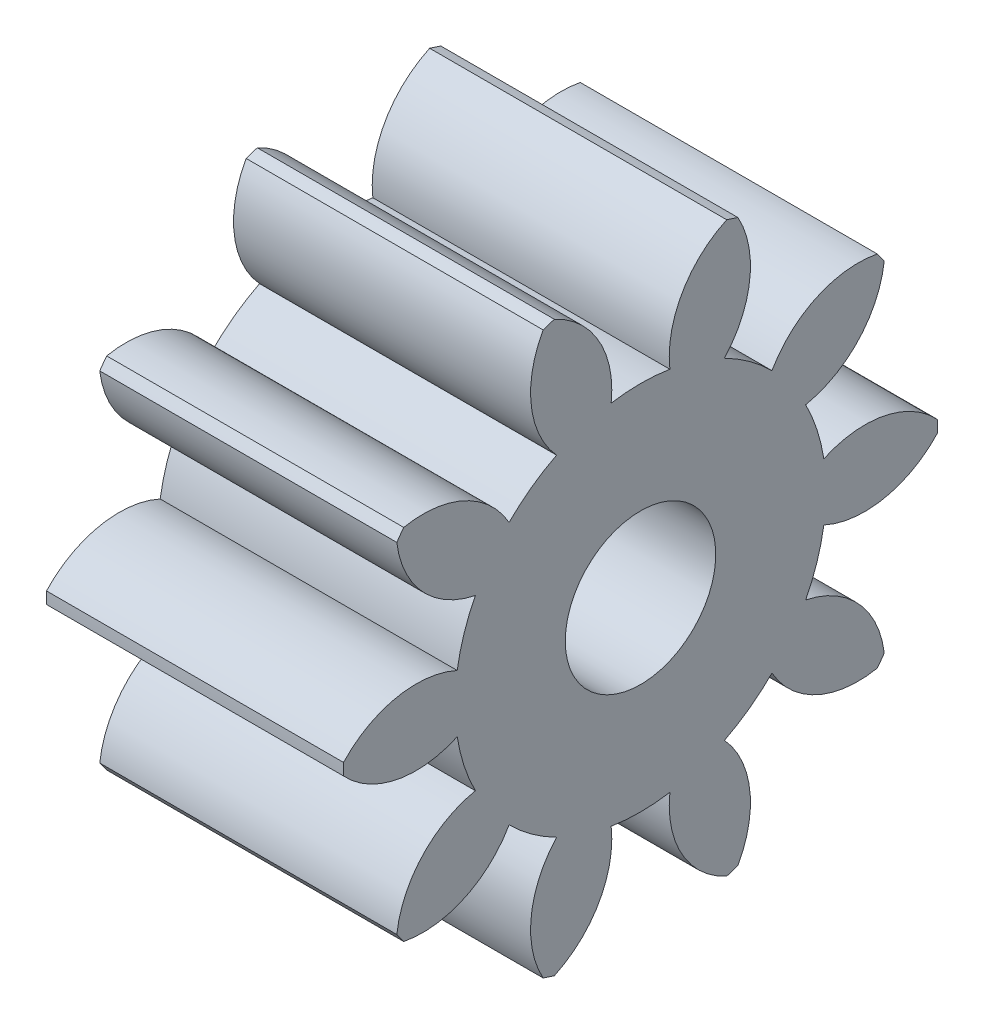
SolidWorks part; units mm, degrees
ref_plane "Plane1" through (0, 0, 0) normal (0, 0, 1) x (1, 0, 0)
ref_plane "Plane2" through (0, 0, 0) normal (0, 1, 0) x (1, 0, 0)
ref_plane "Plane3" through (0, 0, 0) normal (1, 0, 0) x (0, 0, -1)
other "Configuration Table"
sketch "HoldingSke" plane through (0, 0, 0) normal (0, 1, 0) x (1, 0, 0)
  line L0 (0, 0) -> (1.9696, -0.3473)
  line L1 (-15, 0) -> (100, 0) construction
  line L2 (0, 0) -> (-2.1039, 2.3779)
  line L3 (0, 0) -> (-11.863, 4.5341)
  line L4 (0, 0) -> (8.5048, 1.4996)
  line L5 (0, 0) -> (-46.8476, -17.4728)
  line L6 (0, 0) -> (-2.4869, -1.6779)
  line L7 (-2.1039, 2.3779) -> (8.6586, 51.2059)
  line L8 (-76.2, 54.61) -> (-76, 54.61)
  line L9 (-71.009, 38.7566) -> (-53.1078, 45.2721)
  line L10 (-76.2, 71.12) -> (104.1128, 71.12)
  line L11 (0, 0) -> (-3, 0)
  line L12 (-76.2, 101.6) -> (-76.181, 101.6)
  line L13 (24.9733, 27.94) -> (52.9518, 28.4284)
  line L14 (24.9733, 27.94) -> (24.9743, 27.94)
  line L15 (24.9733, 27.94) -> (100.4006, 29.5858)
  line L16 (-63.627, -0.5) -> (-12.827, -0.5)
  circle A0 centre (0, 0) radius 0.75
  circle A1 centre (0, 0) radius 1.874
  circle A2 centre (0, 0) radius 37.5
  circle A3 centre (0, 0) radius 0.75
  dimension "MHD" = 3.748
  dimension "Hub_dia" = 75
  dimension "Bore" = 1.5
  dimension "MBD" = 1.5
  dimension "Num_teeth" = 10
  dimension "Pitch" = 2
  dimension "Overall_len" = 50
  dimension "Show_teeth" = 10
  dimension "Thickness" = 3
  dimension "OAL" = 50.0001
  dimension "T_dim" = 0.2
  dimension "Ap" = 20
  dimension "H" = 19.05
  dimension "Pitch_radius" = 180.3128
  dimension "Width" = 3
  dimension "Backlash" = 0.019
  dimension "Addendum_fac" = 1
  dimension "Dedendum_fac" = 1.25
  dimension "Clearance_fac" = 0.25
  dimension "Dedendum_add" = 0.001
  dimension "Module" = 0.5
sketch "BasProSke" plane through (0, 0, 0) normal (0, 1, 0) x (1, 0, 0)
  line L0 (-10, 0) -> (60, 0) construction
  line L1 (0, 0) -> (0, 3)
  line L2 (0, 0) -> (3, 0)
  line L3 (3, 0) -> (3, 3)
  line L4 (3, 3) -> (0, 3)
  dimension "Thickness" = 3
  dimension "Diameter" = 6
revolve "Base-Revolve" add sketch "BasProSke" angle 360 about L0
sketch "TooCutSke" plane through (0, 0, 0) normal (1, 0, 0) x (0, 0, -1)
  line L1 (0, 0) -> (0, 107) construction
  line L2 (0, 0) -> (-0.4243, 2.4637) construction
  line L3 (0, 0) -> (-1.5292, 4.7063) construction
  line L4 (-0.4243, 2.4637) -> (-0.7646, 2.3532) construction
  arc A0 (0.2964, 1.8504) -> (-0.2964, 1.8504) centre (0, 0) ccw
  arc A1 (0.9059, 2.8866) -> (-0.9059, 2.8866) centre (0, 0) ccw
  circle A2 centre (0, 0) radius 2.5 construction
  circle A3 centre (0, 0) radius 2.3492 construction
  arc A4 (-0.2964, 1.8504) -> (-0.9059, 2.8866) centre (-1.2901, 1.9633) ccw
  arc A5 (0.9059, 2.8866) -> (0.2964, 1.8504) centre (1.2901, 1.9633) ccw
  dimension "Root_dia" = 3.748
  dimension "Overcut_dia" = 6.0508
  dimension "Pitch_dia" = 5
  dimension "Base_dia" = 4.6985
  dimension "Flank_rad" = 1
  dimension "Half_ang" = 18
  dimension "Half_CT" = 0.3578
extrude "ToothCut" cut sketch "TooCutSke" along normal through all
fillet "Breaks" [suppressed] radius 0.01
fillet "RootFillets" [suppressed] radius 0.126
pattern_circular "TeethCuts" count 10 every 36 about axis through (-10, 0, 0) along (1, 0, 0) of "ToothCut", "RootFillets", "Breaks"
sketch "HubNeaOneSke" plane through (0, 0, 0) normal (-1, 0, 0) x (0, 0, 1)
  circle A0 centre (0, 0) radius 1.874
  dimension "Diameter" = 3.748
extrude "HubNearOne" [suppressed] add sketch "HubNeaOneSke" along normal blind 47.0001
sketch "HubNeaBotSke" plane through (0, 0, 0) normal (-1, 0, 0) x (0, 0, 1)
  circle A0 centre (0, 0) radius 1.874
  dimension "Diameter" = 3.748
extrude "HubNearBoth" [suppressed] add sketch "HubNeaBotSke" along normal blind 23.5001
ref_plane "FarPln" through (3, 0, 0) normal (1, 0, 0) x (0, 0, -1)
sketch "HubFarSke" plane through (3, 0, 0) normal (1, 0, 0) x (0, 0, -1)
  circle A0 centre (0, 0) radius 1.874
  dimension "Diameter" = 3.748
extrude "HubFar" [suppressed] add sketch "HubFarSke" along normal blind 23.5001
sketch "BorSke" plane through (0, 0, 0) normal (1, 0, 0) x (0, 0, -1)
  circle A0 centre (0, 0) radius 0.76
  dimension "Diameter" = 1.52
extrude "Bore" cut sketch "BorSke" along normal mid plane 100.0002
sketch "KeySke" plane through (0, 0, 0) normal (1, 0, 0) x (0, 0, -1)
  line L0 (-0.3, 0) -> (-0.3, 0.95)
  line L1 (-0.3, 0.95) -> (0.3, 0.95)
  line L2 (0.3, 0.95) -> (0.3, 0)
  line L3 (0, 0) -> (0, 34) construction
  line L4 (-0.3, 0) -> (0.3, 0)
  dimension "Offset" = 0.95
  dimension "Width" = 0.6
extrude "Keyway" [suppressed] cut sketch "KeySke" along normal mid plane 100.0002
pattern_circular "Keyway2" [suppressed] count 2 every 90 about axis through (-10, 0, 0) along (1, 0, 0)
equation "' \"Module@HoldingSke\" = 6.35"
equation "' \"Num_teeth@HoldingSke\" = 12"
equation "' \"Ap@HoldingSke\" =  20"
equation "' \"Ap@HoldingSke\" = 20"
equation "' \"Width@HoldingSke\" = 0.5 * 25.4"
equation "' \"Hub_dia@HoldingSke\"= 1 * 25.4"
equation "' \"Hub_dia@HoldingSke\" = 1 * 25.4"
equation "' \"Overall_len@HoldingSke\" = 1.0 * 25.4"
equation "' \"Bore@HoldingSke\" = 0.75 * 25.4"
equation "' \"T_dim@HoldingSke\" = 0.1 * 25.4"
equation "' \"Width@KeySke\" = 0.25 * 25.4"
equation "' \"Show_teeth@HoldingSke\" = 13"
equation "' \"Backlash@HoldingSke\" = 0.009 * 25.4"
equation "' \"Addendum_fac@HoldingSke\" = 1.0"
equation "' \"Dedendum_fac@HoldingSke\" = 1.25"
equation "' \"Dedendum_add@HoldingSke\" = 0.00005 * 25.4"
equation "' \"Clearance_fac@HoldingSke\" = 0.25"
equation "\"Pitch@HoldingSke\" = 1 / \"Module@HoldingSke\""
equation "\"Overcut_dia@TooCutSke\" = (\"Num_teeth@HoldingSke\" + 2 * \"Addendum_fac@HoldingSke\") / \"Pitch@HoldingSke\" + 0.002 * 25.4"
equation "\"Pitch_dia@TooCutSke\" = \"Num_teeth@HoldingSke\" / \"Pitch@HoldingSke\""
equation "\"Base_dia@TooCutSke\" = \"Num_teeth@HoldingSke\" / \"Pitch@HoldingSke\" * cos((\"Ap@HoldingSke\"  * 3.14159265 / 180))"
equation "\"Root_dia@TooCutSke\" = (\"Num_teeth@HoldingSke\" + 2) / \"Pitch@HoldingSke\" - 2 * (\"Addendum_fac@HoldingSke\" + \"Dedendum_fac@HoldingSke\") / \"Pitch@HoldingSke\" - \"Dedendum_add@HoldingSke\" * 2"
equation "\"Half_ang@TooCutSke\" = 180 / \"Num_teeth@HoldingSke\""
equation "\"Half_CT@TooCutSke\" = \"Num_teeth@HoldingSke\" / \"Pitch@HoldingSke\" * sin((3.14159265 / 2 / \"Num_teeth@HoldingSke\")) / 2 - 7 * \"Backlash@HoldingSke\" / 4"
equation "\"Flank_rad@TooCutSke\" = \"Num_teeth@HoldingSke\" / \"Pitch@HoldingSke\" / 5"
equation "\"Radius@RootFillets\" = \"Clearance_fac@HoldingSke\" / \"Pitch@HoldingSke\" + \"Dedendum_add@HoldingSke\""
equation "\"Break_rad@Breaks\" = 0.02 / \"Pitch@HoldingSke\""
equation "\"Thickness@HoldingSke\" = \"Width@HoldingSke\""
equation "\"OAL@HoldingSke\" = \"Thickness@HoldingSke\""
equation "\"MHD@HoldingSke\" = (\"Num_teeth@HoldingSke\" + 2) / \"Pitch@HoldingSke\" - 2 * (\"Addendum_fac@HoldingSke\" + \"Dedendum_fac@HoldingSke\")  / \"Pitch@HoldingSke\" - \"Dedendum_add@HoldingSke\" * 2"
equation "\"MBD@HoldingSke\" = (\"Num_teeth@HoldingSke\" + 2) / \"Pitch@HoldingSke\" - 2 * (\"Addendum_fac@HoldingSke\" + \"Dedendum_fac@HoldingSke\")  / \"Pitch@HoldingSke\" - \"Dedendum_add@HoldingSke\" * 2 - 0.002 * 25.4"
equation "\"MHD@HoldingSke\" = ((sgn( \"MHD@HoldingSke\" - \"Hub_dia@HoldingSke\" )-1)*( \"MHD@HoldingSke\" - \"Hub_dia@HoldingSke\" ))/-2+ \"Hub_dia@HoldingSke\""
equation "\"MBD@HoldingSke\" = ((sgn( \"MBD@HoldingSke\" - \"Bore@HoldingSke\" )-1)*( \"MBD@HoldingSke\" - \"Bore@HoldingSke\" ))/-2+ \"Bore@HoldingSke\""
equation "\"OAL@HoldingSke\" = ((sgn( \"OAL@HoldingSke\" - \"Overall_len@HoldingSke\" )+1)*( \"OAL@HoldingSke\" - \"Overall_len@HoldingSke\" ))/2 + \"Overall_len@HoldingSke\" + 0.000002 * 25.4"
equation "\"Num_teeth@TeethCuts\" = int( \"Show_teeth@HoldingSke\" ) + 1"
equation "\"Num_teeth@TeethCuts\" = ((sgn( \"Num_teeth@TeethCuts\" - \"Num_teeth@HoldingSke\" )-1)*( \"Num_teeth@TeethCuts\" - \"Num_teeth@HoldingSke\" ))/-2+ \"Num_teeth@HoldingSke\""
equation "\"Num_teeth@TeethCuts\" = ((sgn( \"Num_teeth@TeethCuts\" - 2.0)+1)*( \"Num_teeth@TeethCuts\" - 2.0))/2 +2.0"
equation "\"Angle@TeethCuts\" = 360.0 / \"Num_teeth@HoldingSke\""
equation "\"Diameter@BasProSke\" = (\"Num_teeth@HoldingSke\" + 2 * \"Addendum_fac@HoldingSke\") / \"Pitch@HoldingSke\""
equation "\"Thickness@BasProSke\"  = \"Thickness@HoldingSke\""
equation "' \"Fillet_rad@BasProSke\" =  \"Thickness@HoldingSke\" * 0.05"
equation "' \"Fillet_rad@BasProSke\" = \"Thickness@HoldingSke\" * 0.05"
equation "\"MHD@HoldingSke\" = ((sgn( \"MHD@HoldingSke\" - \"Root_dia@TooCutSke\" )-1)*( \"MHD@HoldingSke\" - \"Root_dia@TooCutSke\" ))/-2+ \"Root_dia@TooCutSke\""
equation "\"Diameter@HubNeaOneSke\" = \"MHD@HoldingSke\""
equation "\"Length@HubNearOne\" = \"OAL@HoldingSke\" - \"Thickness@BasProSke\""
equation "\"Diameter@HubNeaBotSke\" = \"MHD@HoldingSke\""
equation "\"Length@HubNearBoth\" = ( \"OAL@HoldingSke\" - \"Thickness@BasProSke\" ) / 2.0"
equation "\"Thickness@FarPln\" = \"Thickness@BasProSke\""
equation "\"Diameter@HubFarSke\" = \"MHD@HoldingSke\""
equation "\"Length@HubFar\" = ( \"OAL@HoldingSke\" - \"Thickness@BasProSke\" ) / 2.0"
equation "\"D1@Bore\"= \"OAL@HoldingSke\" * 2.0"
equation "\"D1@Keyway\" = \"OAL@HoldingSke\" * 2.0"
equation "\"Offset@KeySke\" = \"T_dim@HoldingSke\" + \"MBD@HoldingSke\" / 2.0"
